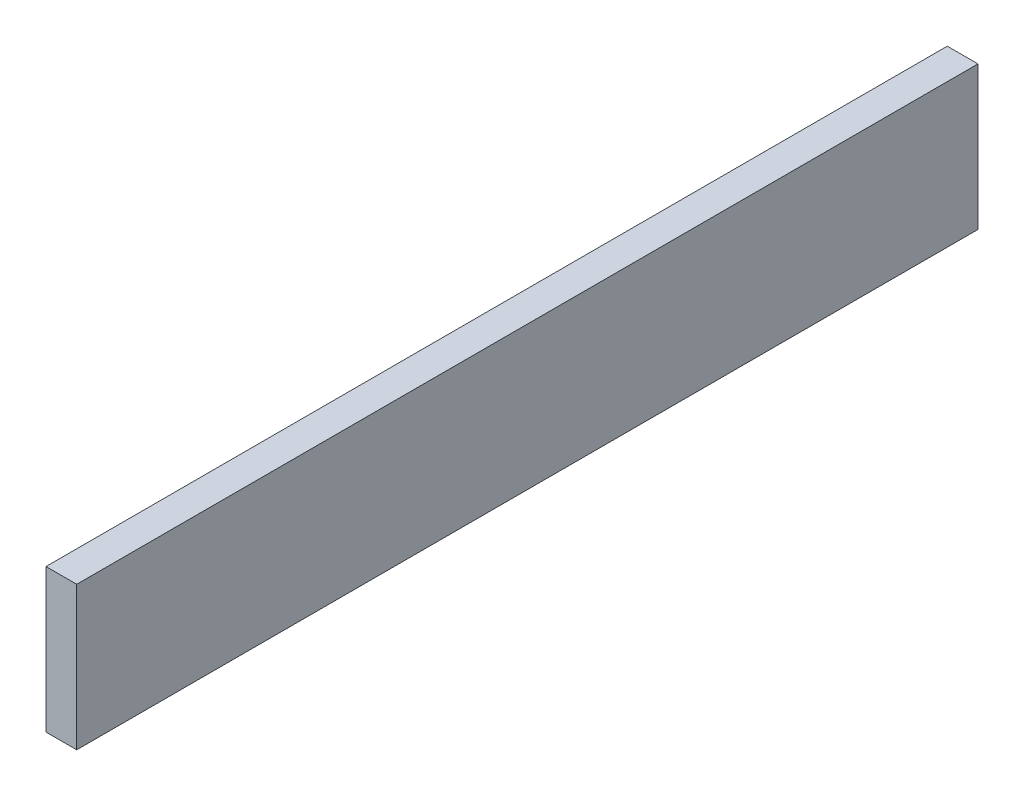
SolidWorks part; units mm, degrees
ref_plane "Front Plane" through (0, 0, 0) normal (0, 0, 1) x (1, 0, 0)
ref_plane "Top Plane" through (0, 0, 0) normal (0, 1, 0) x (1, 0, 0)
ref_plane "Right Plane" through (0, 0, 0) normal (1, 0, 0) x (0, 0, -1)
sketch "Sketch1" plane through (0, 0, 0) normal (0, 0, 1) x (1, 0, 0)
  line L1 (0, 0) -> (19.05, 0)
  line L2 (0, 0) -> (0, 88.9)
  line L3 (0, 88.9) -> (19.05, 88.9)
  line L4 (19.05, 0) -> (19.05, 88.9)
  dimension "D1" = 88.9
  dimension "D2" = 19.05
extrude "Boss-Extrude1" add sketch "Sketch1" along normal blind 558.8
